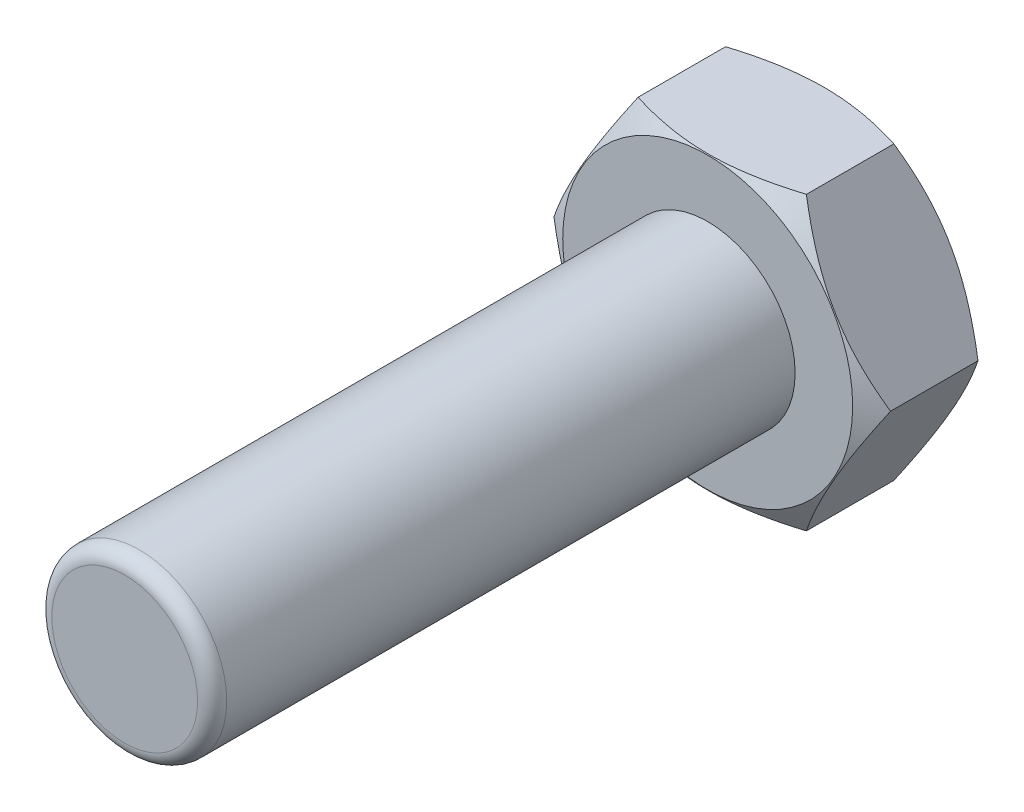
SolidWorks part; units mm, degrees
material "1.0037 (S235JR)"
ref_plane "Ön Düzlem" through (0, 0, 0) normal (0, 0, 1) x (1, 0, 0)
ref_plane "Üst Düzlem" through (0, 0, 0) normal (0, 1, 0) x (1, 0, 0)
ref_plane "Sağ Düzlem" through (0, 0, 0) normal (1, 0, 0) x (0, 0, -1)
sketch "Çizim1" plane through (0, 0, 0) normal (0, 0, 1) x (1, 0, 0)
  line L1 (5.7735, 0) -> (2.8868, 5)
  line L2 (2.8868, 5) -> (-2.8868, 5)
  line L3 (-2.8868, 5) -> (-5.7735, 0)
  line L4 (-5.7735, 0) -> (-2.8868, -5)
  line L5 (-2.8868, -5) -> (2.8868, -5)
  line L6 (2.8868, -5) -> (5.7735, 0)
  circle A0 centre (0, 0) radius 5 construction
  dimension "D1" = 10
extrude "Yükseklik-Ekstrüzyon1" add sketch "Çizim1" along normal blind 4
sketch "Çizim2" plane through (0, 0, 0) normal (0, 1, 0) x (1, 0, 0)
  line L0 (-5.7735, 0) -> (-5.7735, -0.5)
  line L1 (-5.7735, -4) -> (-5.7735, 0) construction
  line L2 (-5.7735, -0.5) -> (-4.9735, 0)
  line L3 (-2.8868, 0) -> (-5.7735, 0) construction
  line L4 (-4.9735, 0) -> (-5.7735, 0)
  line L5 (-5.7735, -4) -> (-5.7735, -3.5)
  line L6 (-5.7735, -3.5) -> (-4.9735, -4)
  line L7 (-2.8868, -4) -> (-5.7735, -4) construction
  line L8 (-4.9735, -4) -> (-5.7735, -4)
  line L9 (0, 0) -> (0, -4) construction
  line L10 (2.8868, -4) -> (-2.8868, -4) construction
  dimension "D1" = 0.8
  dimension "D2" = 0.5
  dimension "D3" = 0.8
  dimension "D4" = 0.5
revolve "Kes-Döndür1" cut sketch "Çizim2" angle 360 about L9
sketch "Çizim3" plane through (0, 0, 4) normal (0, 0, 1) x (1, 0, 0)
  circle A0 centre (0, 0) radius 3
  dimension "D1" = 6
extrude "Yükseklik-Ekstrüzyon2" add sketch "Çizim3" along normal blind 20
cosmetic thread "Kozmetik Diş Açma1" parameters "D2"=4.891
fillet "Radyus1" radius 0.5 1 edges at (3, 0, 24)
